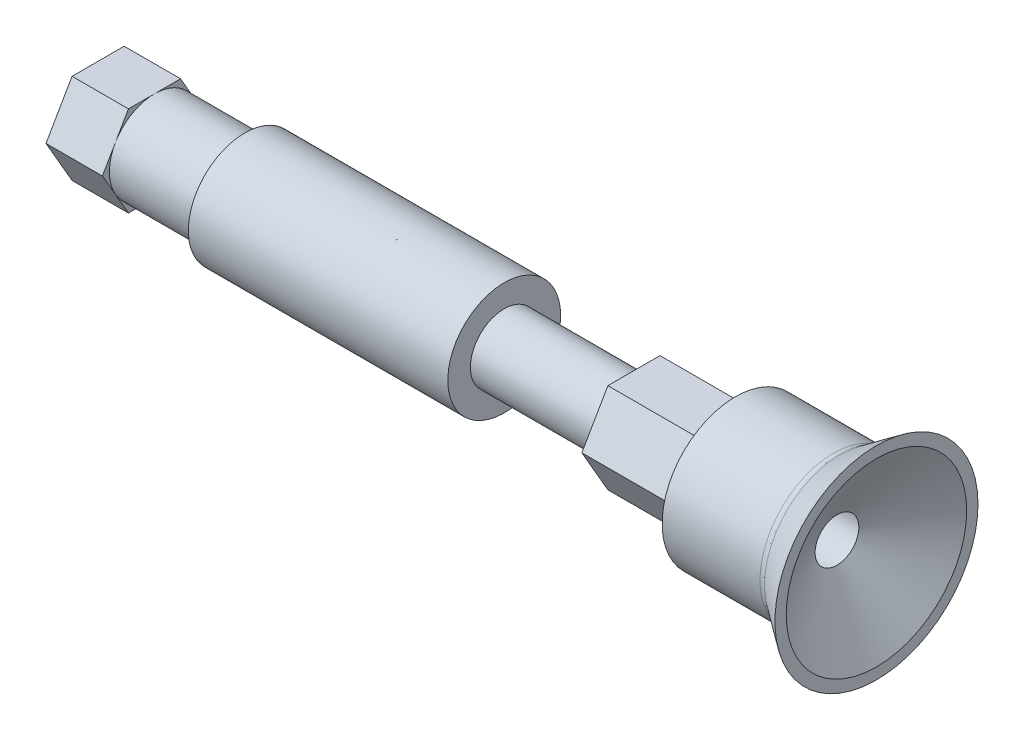
SolidWorks part; units mm, degrees
ref_plane "前视基准面" through (0, 0, 0) normal (0, 0, 1) x (1, 0, 0)
ref_plane "上视基准面" through (0, 0, 0) normal (0, 1, 0) x (1, 0, 0)
ref_plane "右视基准面" through (0, 0, 0) normal (1, 0, 0) x (0, 0, -1)
sketch "草图1" plane through (0, 0, 0) normal (1, 0, 0) x (0, 0, -1)
  line L1 (2.3094, 4) -> (-2.3094, 4)
  line L2 (-2.3094, 4) -> (-4.6188, 0)
  line L3 (-4.6188, 0) -> (-2.3094, -4)
  line L4 (-2.3094, -4) -> (2.3094, -4)
  line L5 (2.3094, -4) -> (4.6188, 0)
  line L6 (4.6188, 0) -> (2.3094, 4)
  circle A0 centre (0, 0) radius 4 construction
  dimension "D1" = 8
extrude "凸台-拉伸1" add sketch "草图1" along normal blind 5
sketch "草图2" plane through (5, 0, 0) normal (1, 0, 0) x (0, 0, -1)
  circle A0 centre (0, 0) radius 4
  dimension "D1" = 8
extrude "凸台-拉伸2" add sketch "草图2" along normal blind 8
sketch "草图3" plane through (13, 0, 0) normal (1, 0, 0) x (0, 0, -1)
  circle A0 centre (0, 0) radius 5
  dimension "D1" = 10
extrude "凸台-拉伸3" add sketch "草图3" along normal blind 23
cosmetic thread "装饰螺纹线1" parameters "D2"=8.891
sketch "草图4" plane through (36, 0, 0) normal (1, 0, 0) x (0, 0, -1)
  circle A0 centre (0, 0) radius 3
  dimension "D1" = 6
extrude "凸台-拉伸4" add sketch "草图4" along normal blind 11.5
sketch "草图5" plane through (47.5, 0, 0) normal (1, 0, 0) x (0, 0, -1)
  line L1 (2.3094, 4) -> (-2.3094, 4)
  line L2 (-2.3094, 4) -> (-4.6188, 0)
  line L3 (-4.6188, 0) -> (-2.3094, -4)
  line L4 (-2.3094, -4) -> (2.3094, -4)
  line L5 (2.3094, -4) -> (4.6188, 0)
  line L6 (4.6188, 0) -> (2.3094, 4)
  circle A0 centre (0, 0) radius 4 construction
  dimension "D1" = 8
extrude "凸台-拉伸5" add sketch "草图5" along normal blind 9
sketch "草图6" plane through (0, 0, 0) normal (-1, 0, 0) x (0, 0, 1)
  circle A0 centre (0, 0) radius 2.5
  dimension "D1" = 5
extrude "切除-拉伸1" cut sketch "草图6" against normal blind 5
cosmetic thread "装饰螺纹线2" parameters "D2"=6
sketch "草图7" plane through (5, 0, 0) normal (-1, 0, 0) x (0, 0, 1)
  circle A0 centre (0, 0) radius 2
  dimension "D1" = 4
extrude "切除-拉伸2" cut sketch "草图7" against normal blind 8
cosmetic thread "装饰螺纹线3" parameters "D2"=5
sketch "草图8" plane through (13, 0, 0) normal (-1, 0, 0) x (0, 0, 1)
  circle A0 centre (0, 0) radius 2.5
  dimension "D1" = 5
extrude "切除-拉伸3" cut sketch "草图8" against normal through all
sketch "草图9" plane through (56.5, 0, 0) normal (1, 0, 0) x (0, 0, -1)
  circle A0 centre (0, 0) radius 6.5
  dimension "D1" = 13
extrude "凸台-拉伸6" add sketch "草图9" along normal blind 9
ref_axis "基准轴1" through (65.5, 0, 0) along (-1, 0, 0)
ref_plane "基准面1" through (0, 0, 0) normal (0, 0, -1) x (-1, 0, 0)
sketch "草图10" plane through (0, 0, 0) normal (0, 0, -1) x (-1, 0, 0)
  line L0 (-65.5, 0) -> (-69, 0) construction
  line L1 (-65.5, 6.5) -> (-65.5, -6.5) construction
  line L2 (-65.5, 0) -> (-56.5, 0) construction
  line L3 (-69, 0) -> (-69, 9)
  line L4 (-65.5, 0) -> (-65.5, 6.5)
  line L5 (-65.5, 6.5) -> (-69, 9)
  line L6 (-69, 9) -> (-68.8384, 8.9596)
  line L7 (-65.5, 0) -> (-69, 0)
  dimension "D1" = 9
  dimension "D2" = 3.5
revolve "旋转1" add sketch "草图10" angle 360 about axis through (65.5, 0, 0) along (-1, 0, 0)
fillet "圆角1" radius 1 1 edges at (65.5, 0, -6.5)
sketch "草图11" plane through (69, 0, 0) normal (1, 0, 0) x (0, 0, -1)
  circle A0 centre (0, 0) radius 8
  dimension "D1" = 16
extrude "切除-拉伸4" cut sketch "草图11" against normal blind 3.5 draft 60
sketch "草图12" plane through (65.5, 0, 0) normal (1, 0, 0) x (0, 0, -1)
  circle A0 centre (0, 0) radius 2.5
  dimension "D1" = 5
extrude "切除-拉伸5" cut sketch "草图12" against normal blind 10
